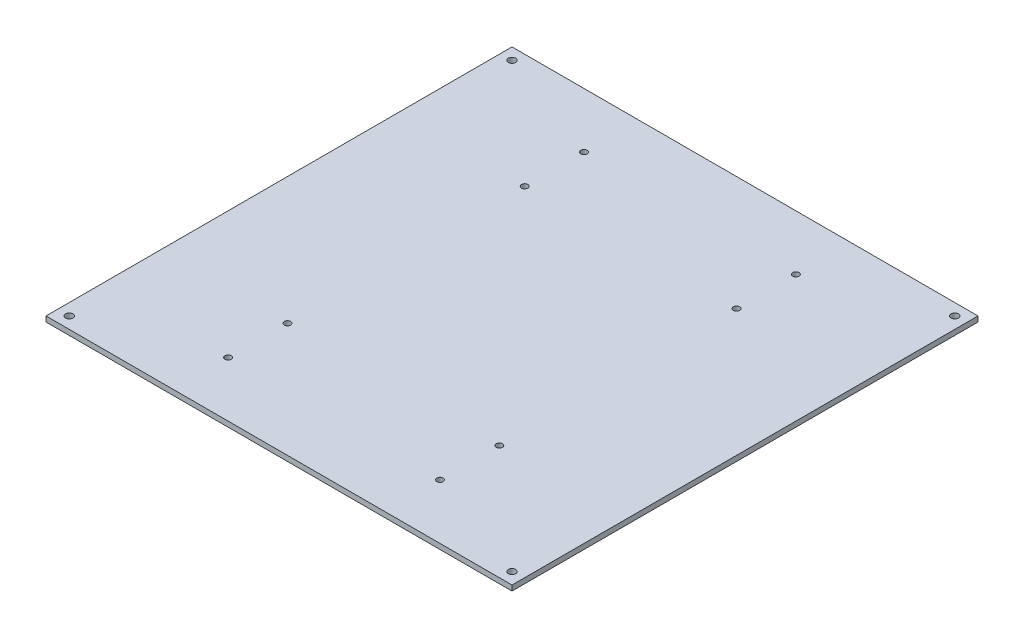
SolidWorks part; units mm, degrees
ref_plane "前视基准面" through (0, 0, 0) normal (0, 0, 1) x (1, 0, 0)
ref_plane "上视基准面" through (0, 0, 0) normal (0, 1, 0) x (1, 0, 0)
ref_plane "右视基准面" through (0, 0, 0) normal (1, 0, 0) x (0, 0, -1)
sketch "草图1" plane through (0, 0, 0) normal (0, 1, 0) x (1, 0, 0)
  line L1 (0, 0) -> (220, 0)
  line L2 (0, 0) -> (0, 220)
  line L3 (0, 220) -> (220, 220)
  line L4 (220, 0) -> (220, 220)
  line L5 (0, 0) -> (220, 220) construction
  line L6 (0, 220) -> (220, 0) construction
  line L7 (5.5, 214.5) -> (214.5, 214.5) construction
  line L8 (5.5, 214.5) -> (5.5, 5.5) construction
  line L9 (5.5, 5.5) -> (214.5, 5.5) construction
  line L10 (214.5, 214.5) -> (214.5, 5.5) construction
  line L11 (110, 5.5) -> (110, 214.5) construction
  line L12 (5.5, 110) -> (214.5, 110) construction
  circle A0 centre (5.5, 5.5) radius 1.75
  circle A1 centre (214.5, 5.5) radius 1.75
  circle A2 centre (214.5, 214.5) radius 1.75
  circle A3 centre (5.5, 214.5) radius 1.75
  point P4 (110, 110)
  point P6 (110, 110)
  dimension "D4" = 3.5
  dimension "D1" = 220
  dimension "D2" = 220
  dimension "D3" = 209
extrude "凸台-拉伸1" add sketch "草图1" along normal blind 2.5
sketch "草图2" plane through (0, 0, 0) normal (0, -1, 0) x (1, 0, 0)
  line L0 (60, 0) -> (60, -220) construction
  line L1 (0, 0) -> (220, 0) construction
  line L2 (220, -220) -> (0, -220) construction
  line L3 (0, -220) -> (0, 0) construction
  line L4 (110, 0) -> (110, -220) construction
  line L5 (0, -110) -> (220, -110) construction
  line L6 (220, 0) -> (220, -220) construction
  circle A0 centre (60, -26) radius 1.5
  circle A1 centre (60, -54) radius 1.5
  circle A2 centre (60, -166) radius 1.5
  circle A3 centre (60, -194) radius 1.5
  circle A4 centre (160, -194) radius 1.5
  circle A5 centre (160, -166) radius 1.5
  circle A6 centre (160, -54) radius 1.5
  circle A7 centre (160, -26) radius 1.5
  dimension "D1" = 3
  dimension "D2" = 3
  dimension "D3" = 28
  dimension "D4" = 26
  dimension "D5" = 60
extrude "切除-拉伸1" cut sketch "草图2" against normal through all
